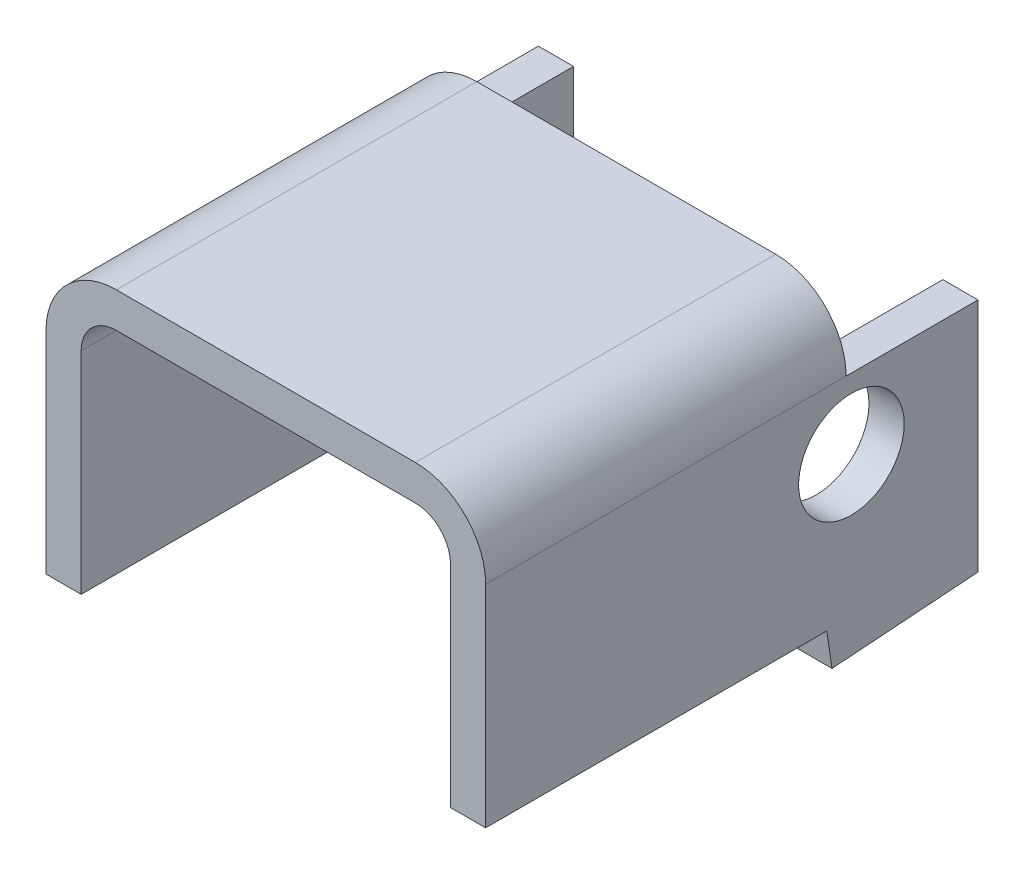
SolidWorks part; units mm, degrees
ref_plane "Front Plane" through (0, 0, 0) normal (0, 0, 1) x (1, 0, 0)
ref_plane "Top Plane" through (0, 0, 0) normal (0, 1, 0) x (1, 0, 0)
ref_plane "Right Plane" through (0, 0, 0) normal (1, 0, 0) x (0, 0, -1)
ref_plane "Plane1" through (-11.5, 0, 0) normal (-1, 0, 0) x (0, 0, 1)
sketch "Sketch1" plane through (0, 0, 0) normal (1, 0, 0) x (0, 0, -1)
  line L0 (0, 0) -> (0, 6)
  line L1 (0, 6) -> (14, 6)
  line L2 (14, 6) -> (14, -0.7)
  line L3 (14, -0.7) -> (9.85, -1)
  line L4 (9.85, -1) -> (9.7, 0)
  line L5 (9.7, 0) -> (0, 0)
  circle A0 centre (10.4, 4) radius 1.5
  dimension "D7" = 3
  dimension "D1" = 6
  dimension "D2" = 1
  dimension "D3" = 9.85
  dimension "D4" = 0.15
  dimension "D5" = 14
  dimension "D6" = 0.3
  dimension "D8" = 2
  dimension "D9" = 3.6
extrude "Boss-Extrude1" add sketch "Sketch1" against normal mid plane 1
sketch "Sketch2" plane through (-11.5, 0, 0) normal (-1, 0, 0) x (0, 0, 1)
  line L0 (-9.7, 0) -> (-9.85, -1) construction
  line L1 (0, 0) -> (-9.7, 0) construction
  line L2 (0, 6) -> (0, 0) construction
  line L3 (-14, 6) -> (0, 6) construction
  line L4 (-14, -0.7) -> (-14, 6) construction
  line L5 (-9.85, -1) -> (-14, -0.7) construction
  line L6 (-9.7, 0) -> (-9.85, -1)
  line L7 (0, 0) -> (-9.7, 0)
  line L8 (0, 6) -> (0, 0)
  line L9 (-14, 6) -> (0, 6)
  line L10 (-14, -0.7) -> (-14, 6)
  line L11 (-9.85, -1) -> (-14, -0.7)
  circle A0 centre (-10.4, 4) radius 1.5 construction
  circle A1 centre (-10.4, 4) radius 1.5
extrude "Boss-Extrude2" add sketch "Sketch2" against normal mid plane 1 separate body
sketch "Sketch9" plane through (0, 0, 0) normal (0, 0, 1) x (1, 0, 0)
  line L0 (-11, 6) -> (-12, 6)
  line L1 (-10, 8) -> (-1.5, 8)
  line L2 (0.5, 6) -> (-0.5, 6)
  line L3 (-1.5, 7) -> (-10, 7)
  arc A0 (-12, 6) -> (-10, 8) centre (-10, 6) cw
  arc A1 (-1.5, 8) -> (0.5, 6) centre (-1.5, 6) cw
  arc A2 (-0.5, 6) -> (-1.5, 7) centre (-1.5, 6) ccw
  arc A3 (-10, 7) -> (-11, 6) centre (-10, 6) ccw
  dimension "D1" = 2
extrude "Boss-Extrude6" add sketch "Sketch9" against normal blind 10.25
